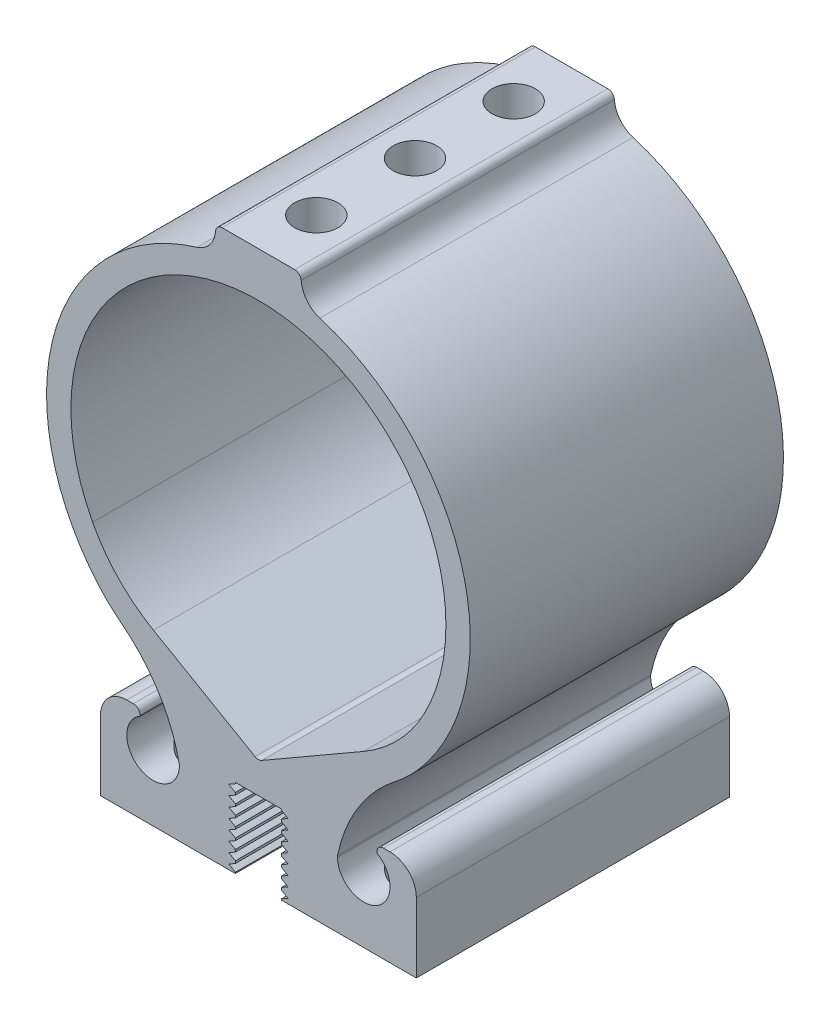
SolidWorks part; units mm, degrees
material "Alliage 6061"
ref_plane "Face" through (0, 0, 0) normal (0, 0, 1) x (1, 0, 0)
ref_plane "Dessus" through (0, 0, 0) normal (0, 1, 0) x (1, 0, 0)
ref_plane "Droite" through (0, 0, 0) normal (1, 0, 0) x (0, 0, -1)
sketch "Esquisse1" plane through (0, 0, 0) normal (0, 0, 1) x (1, 0, 0)
  line L0 (-45.6611, 0) -> (55.5494, 0) construction
  line L1 (-12, 0) -> (12, 0)
  line L2 (12, 0) -> (12, 7.3)
  line L3 (12, 7.3) -> (9, 7.3)
  line L4 (9, 7.3) -> (9, 6.7321)
  line L6 (0, 0) -> (0, 24.35) construction
  line L7 (-12, 0) -> (-12, 7.3)
  line L8 (-12, 7.3) -> (-9, 7.3)
  line L9 (-9, 7.3) -> (-9, 6.7321)
  line L11 (-3.25, 42) -> (3.25, 42)
  line L12 (-3.25, 42) -> (-3.25, 40.1186)
  line L13 (3.25, 42) -> (3.25, 40.1186)
  line L14 (0, 8.3) -> (-9.6466, 13.8616)
  line L15 (0, 8.3) -> (9.6466, 13.8616)
  line L16 (0, 24.35) -> (-10.899, 12.5) construction
  arc A0 (9.6466, 13.8616) -> (-9.6466, 13.8616) centre (0, 24.35) ccw
  arc A1 (-3.25, 40.1186) -> (-10.899, 12.5) centre (0, 24.35) ccw
  arc A2 (6, 5) -> (9, 6.7321) centre (8, 5) ccw
  arc A3 (-6, 5) -> (-9, 6.7321) centre (-8, 5) cw
  arc A4 (10.899, 12.5) -> (3.25, 40.1186) centre (0, 24.35) ccw
  arc A5 (10.899, 12.5) -> (6, 5) centre (17.77, 2.6619) ccw
  arc A6 (-10.899, 12.5) -> (-6, 5) centre (-17.77, 2.6619) cw
  dimension "D1" = 28.5
  dimension "D2" = 32.2
  dimension "D4" = 3.4
  dimension "D5" = 4
  dimension "D7" = 16
  dimension "D9" = 3
  dimension "D14" = 12
  dimension "D3" = 42
  dimension "D6" = 7.3
  dimension "D8" = 24
  dimension "D10" = 3
  dimension "D11" = 6.5
  dimension "D12" = 12.5
  dimension "D13" = 8.3
extrude "Boss.-Extru.1" add sketch "Esquisse1" along normal mid plane 23.8
sketch "Esquisse2" plane through (0, 0, 11.9) normal (0, 0, 1) x (1, 0, 0)
  line L0 (0, 0) -> (0, 10.1) construction
  line L1 (-12, 0) -> (12, 0) construction
  line L3 (-1.75, 0) -> (1.75, 0)
  line L4 (-1.75, 0) -> (-1.75, 6)
  line L5 (-1.75, 6) -> (1.75, 6)
  line L6 (1.75, 0) -> (1.75, 6)
  circle A0 centre (0, 24.35) radius 14.25 construction
  dimension "D1" = 3.5
  dimension "D2" = 6
extrude "Enlèv. mat.-Extru.1" cut sketch "Esquisse2" against normal through all
fillet "Congé1" radius 2 4 edges at (12, 7.3, 0) (-12, 7.3, 0) (-3.25, 40.1186, 0) (3.25, 40.1186, 0)
fillet "Congé2" radius 12 4 edges at (10.899, 12.5, 0) (-10.899, 12.5, 0) (9.6466, 13.8616, 0) (-9.6466, 13.8616, 0)
fillet "Congé3" radius 0.5 7 edges at (3.25, 42, 0) (-3.25, 42, 0) (-6, 5, 0) (-9, 7.3, 0) (9, 7.3, 0) (6, 5, 0) (0, 8.3, 0)
hole_wizard "Trou taraudé M41" positions "Esquisse5" profile "Esquisse4" tap size "M4" standard "Iso"
sketch "Esquisse5" plane through (0, 42, 0) normal (0, 1, 0) x (1, 0, 0)
  line L0 (0, 10.5623) -> (0, -10.5623) construction
  line L1 (-3.2547, 0) -> (3.2547, 0) construction
  line L2 (3.2547, 11.9) -> (3.2547, -11.9) construction
  line L4 (-3.2547, -11.9) -> (-3.2547, 11.9) construction
  point P0 (0, 0)
  point P3 (0, 7.5)
  point P5 (0, -7.5)
  dimension "D1" = 15
cosmetic thread "Filetage de perçage1" parameters "D2"=4
cosmetic thread "Filetage de perçage2" parameters "D2"=4
cosmetic thread "Filetage de perçage3" parameters "D2"=4
sketch "Esquisse4" plane through (0, 42, 0) normal (1, 0, 0) x (0, 0, 1)
  line L0 (0, 0) -> (0, 3.4)
  line L1 (0, 3.4) -> (1.65, 3.4)
  line L2 (1.65, 3.4) -> (1.65, 0)
  line L5 (1.65, 0) -> (0, 0)
  line L11 (0, -6.35) -> (0, 107.95) construction
  dimension "Diamètre du trou pour taraudage jusqu'au prochain" = 3.3
  dimension "Profondeur du trou pour taraudage jusqu'au prochain" = 3.4
hole_wizard "Trou taraudé M42" positions "Esquisse7" profile "Esquisse6" tap size "M4" standard "Iso"
sketch "Esquisse7" plane through (0, 0, 0) normal (0, -1, 0) x (-1, 0, 0)
  line L0 (0, 0) -> (0, -19.9183) construction
  line L1 (0, 0) -> (-19.8884, 0) construction
  point P0 (8, -8)
  point P2 (8, 8)
  point P4 (-8, 8)
  point P6 (-8, -8)
  dimension "D1" = 16
  dimension "D2" = 16
sketch "Esquisse6" plane through (-8, 0, 8) normal (1, 0, 0) x (0, 0, -1)
  line L0 (0, 0) -> (0, 3)
  line L1 (0, 3) -> (1.65, 3)
  line L2 (1.65, 3) -> (1.65, 0)
  line L5 (1.65, 0) -> (0, 0)
  line L11 (0, -6.35) -> (0, 107.95) construction
  dimension "Diamètre du trou pour taraudage jusqu'au prochain" = 3.3
  dimension "Profondeur du trou pour taraudage jusqu'au prochain" = 3
cosmetic thread "Filetage de perçage4" parameters "D2"=4
cosmetic thread "Filetage de perçage5" parameters "D2"=4
cosmetic thread "Filetage de perçage6" parameters "D2"=4
cosmetic thread "Filetage de perçage7" parameters "D2"=4
sketch "Esquisse8" plane through (0, 0, 11.9) normal (0, 0, 1) x (1, 0, 0)
  line L0 (-1.75, 0.3737) -> (-3.8531, 0.3737) construction
  line L1 (-1.75, 6) -> (-1.75, 0) construction
  line L2 (-1.75, 0.6624) -> (-2.25, 0.3737)
  line L3 (-2.25, 0.3737) -> (-1.75, 0.085)
  line L4 (-1.75, 0.085) -> (-1.75, 0.6624)
  dimension "D1" = 0.5
  dimension "D2" = 60
  dimension "D3" = 0.085
extrude "Enlèv. mat.-Extru.2" cut sketch "Esquisse8" against normal through all
pattern_linear "Répétition linéaire1" count 8 spacing 0.75 along (0, 1, 0) of "Enlèv. mat.-Extru.2"
mirror "Symétrie1" about plane through (0, 0, 0) normal (1, 0, 0) of "Répétition linéaire1", "Enlèv. mat.-Extru.2"
